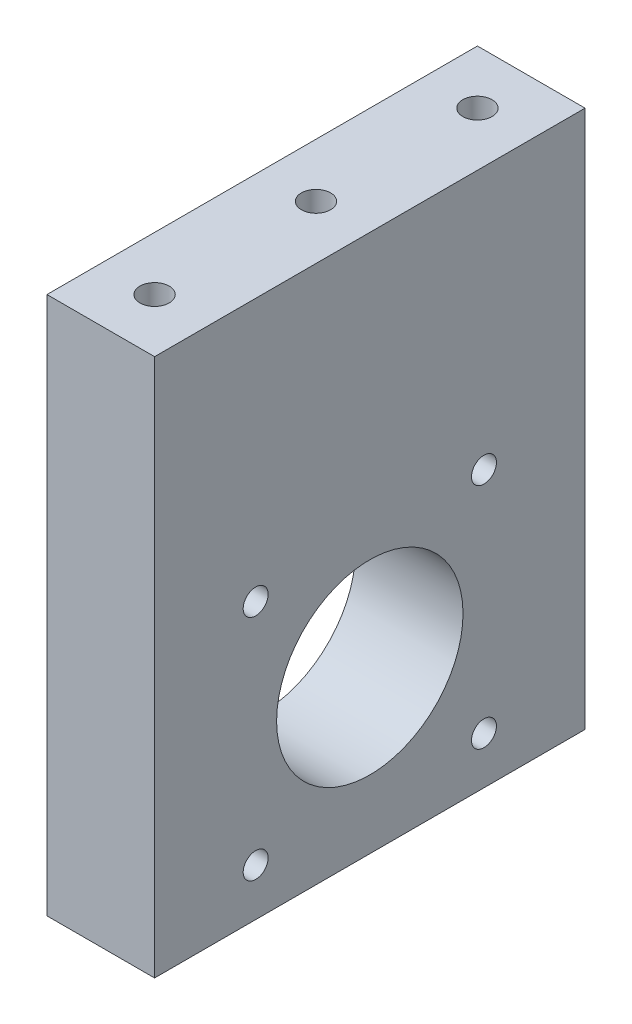
SolidWorks part; units mm, degrees
ref_plane "Front Plane" through (0, 0, 0) normal (0, 0, 1) x (1, 0, 0)
ref_plane "Top Plane" through (0, 0, 0) normal (0, 1, 0) x (1, 0, 0)
ref_plane "Right Plane" through (0, 0, 0) normal (1, 0, 0) x (0, 0, -1)
sketch "Sketch1" plane through (0, 0, 0) normal (1, 0, 0) x (0, 0, -1)
  line L1 (-25.4, -31.75) -> (25.4, -31.75)
  line L2 (-25.4, -31.75) -> (-25.4, 31.75)
  line L3 (-25.4, 31.75) -> (25.4, 31.75)
  line L4 (25.4, -31.75) -> (25.4, 31.75)
  line L5 (-25.4, -31.75) -> (25.4, 31.75) construction
  line L6 (-25.4, 31.75) -> (25.4, -31.75) construction
  point P0 (0, 0)
  dimension "D1" = 50.8
  dimension "D2" = 63.5
extrude "Boss-Extrude1" add sketch "Sketch1" along normal blind 12.7
hole_wizard "Ø22.0 (22) Diameter Hole1" positions "Sketch3" profile "Sketch2" hole size "Ø22.0" standard "ANSI Metric" end condition through all
sketch "Sketch3" plane through (12.7, 0, 0) normal (1, 0, 0) x (0, 0, -1)
  line L1 (25.4, 31.75) -> (-25.4, 31.75) construction
  line L2 (0, -31.75) -> (0, 31.75) construction
  line L3 (-25.4, -31.75) -> (25.4, -31.75) construction
  point P0 (0, -12.7)
  dimension "D1" = 44.45
sketch "Sketch2" plane through (12.7, -12.7, 0) normal (0, 1, 0) x (0, 0, -1)
  line L0 (0, 0) -> (0, 12.7)
  line L1 (0, 12.7) -> (11, 12.7)
  line L2 (11, 12.7) -> (11, 0)
  line L5 (11, 0) -> (0, 0)
  line L11 (0, -6.35) -> (0, 107.95) construction
  dimension "Thru Hole Dia." = 22
  dimension "Thru Hole Depth" = 12.7
hole_wizard "#8-32 Tapped Hole1" positions "Sketch12" profile "Sketch11" tap size "#8-32" standard "ANSI Inch"
sketch "Sketch12" plane through (0, 31.75, 0) normal (0, 1, 0) x (1, 0, 0)
  line L0 (6.35, 25.4) -> (6.35, -25.4) construction
  line L1 (12.7, 25.4) -> (0, 25.4) construction
  line L2 (12.7, -25.4) -> (0, -25.4) construction
  line L3 (12.7, 0) -> (0, 0) construction
  line L4 (12.7, 25.4) -> (12.7, -25.4) construction
  line L5 (0, 25.4) -> (0, -25.4) construction
  point P0 (6.35, 19.05)
  point P2 (6.35, -19.05)
  point P13 (6.35, 0)
  dimension "D1" = 6.35
  dimension "D2" = 6.35
sketch "Sketch11" plane through (6.35, 31.75, -19.05) normal (1, 0, 0) x (0, 0, 1)
  line L0 (0, 0) -> (0, 11.7058)
  line L1 (0, 11.7058) -> (1.7272, 10.668)
  line L2 (1.7272, 10.668) -> (1.7272, 0)
  line L5 (1.7272, 0) -> (0, 0)
  line L10 (0, 11.7058) -> (-1.7272, 10.668) construction
  line L11 (0, -6.35) -> (0, 107.95) construction
  dimension "Tap Drill Dia." = 3.4544
  dimension "Tap Drill Depth" = 10.668
  dimension "Drill Angle" = 118
hole_wizard "#4 Clearance Hole1" positions "Sketch14" profile "Sketch13" hole size "#4" standard "ANSI Inch" end condition through all
sketch "Sketch14" plane through (0, 0, 0) normal (-1, 0, 0) x (0, 0, 1)
  line L0 (0, 31.75) -> (0, -31.75) construction
  line L1 (-25.4, 31.75) -> (25.4, 31.75) construction
  line L2 (25.4, -31.75) -> (-25.4, -31.75) construction
  line L3 (0, -12.7) -> (-13.4704, 0.7704) construction
  circle A1 centre (0, -12.7) radius 11 construction
  circle A2 centre (0, -12.7) radius 11
  point P0 (-13.4704, 0.7704)
  dimension "D1" = 19.05
  dimension "D2" = 45
sketch "Sketch13" plane through (0, 0.7704, -13.4704) normal (0, 1, 0) x (0, 0, 1)
  line L0 (0, 0) -> (0, 12.7)
  line L1 (0, 12.7) -> (1.4732, 12.7)
  line L2 (1.4732, 12.7) -> (1.4732, 0)
  line L5 (1.4732, 0) -> (0, 0)
  line L11 (0, -6.35) -> (0, 107.95) construction
  dimension "Thru Hole Dia." = 2.9464
  dimension "Thru Hole Depth" = 12.7
pattern_circular "CirPattern1" count 4 over 360 about axis through (0, -12.7, 0) along (1, 0, 0) of "#4 Clearance Hole1"
